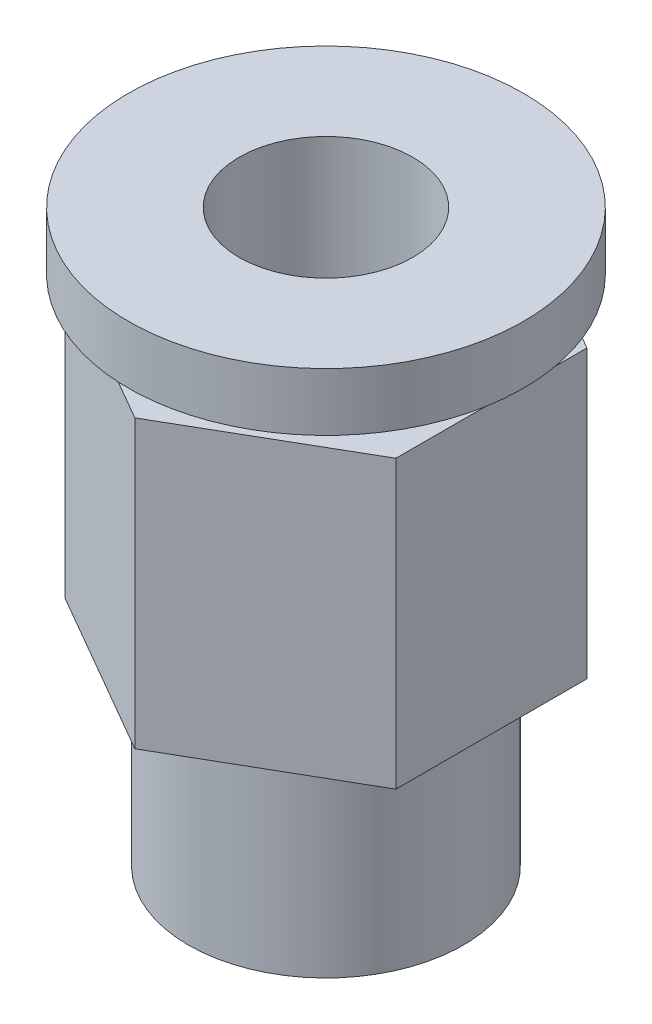
SolidWorks part; units mm, degrees
ref_plane "Front Plane" through (0, 0, 0) normal (0, 0, 1) x (1, 0, 0)
ref_plane "Top Plane" through (0, 0, 0) normal (0, 1, 0) x (1, 0, 0)
ref_plane "Right Plane" through (0, 0, 0) normal (1, 0, 0) x (0, 0, -1)
sketch "Sketch1" plane through (0, 0, 0) normal (0, 0, 1) x (1, 0, 0)
  line L0 (0, 0) -> (0, 25.3333) construction
  line L1 (-4.75, 0) -> (-4.75, 6.8)
  line L2 (-4.75, 6.8) -> (-6.6, 6.8)
  line L3 (-6.6, 6.8) -> (-6.6, 16.7)
  line L4 (-6.6, 16.7) -> (-4, 16.7)
  line L5 (-4, 16.7) -> (-4, 17.7)
  line L6 (-4, 17.7) -> (-6.825, 17.7)
  line L7 (-6.825, 17.7) -> (-6.825, 19.7)
  line L8 (-6.825, 19.7) -> (-3, 19.7)
  line L9 (-3, 19.7) -> (-3, 0)
  line L10 (-3, 0) -> (-4.75, 0)
  point P13 (-4, 17.2)
  dimension "D1" = 9.5
  dimension "D2" = 13.2
  dimension "D3" = 8
  dimension "D4" = 13.65
  dimension "D5" = 6.8
  dimension "D6" = 9.9
  dimension "D7" = 1
  dimension "D8" = 2
  dimension "D9" = 6
revolve "Revolve1" add sketch "Sketch1" angle 360 about L0
sketch "Sketch2" plane through (0, 6.8, 0) normal (0, -1, 0) x (1, 0, 0)
  line L0 (0, 0) -> (0, 6.6) construction
  line L1 (0, 6.6) -> (-5.7158, 3.3)
  line L2 (-5.7158, 3.3) -> (-5.7158, -3.3)
  line L3 (-5.7158, -3.3) -> (0, -6.6)
  line L4 (0, -6.6) -> (5.7158, -3.3)
  line L5 (5.7158, -3.3) -> (5.7158, 3.3)
  line L6 (5.7158, 3.3) -> (0, 6.6)
  circle A0 centre (0, 0) radius 5.7158 construction
  circle A1 centre (0, 0) radius 6.6 construction
  circle A2 centre (0, 0) radius 6.6
  point P1 (0, 0)
  circle M2 centre (0, 0) radius 6.6
extrude "Cut-Extrude1" cut sketch "Sketch2" against normal up to next contours L1 M2 | L6 M2 | L5 M2 | L4 M2 | L3 M2 | L2 M2
